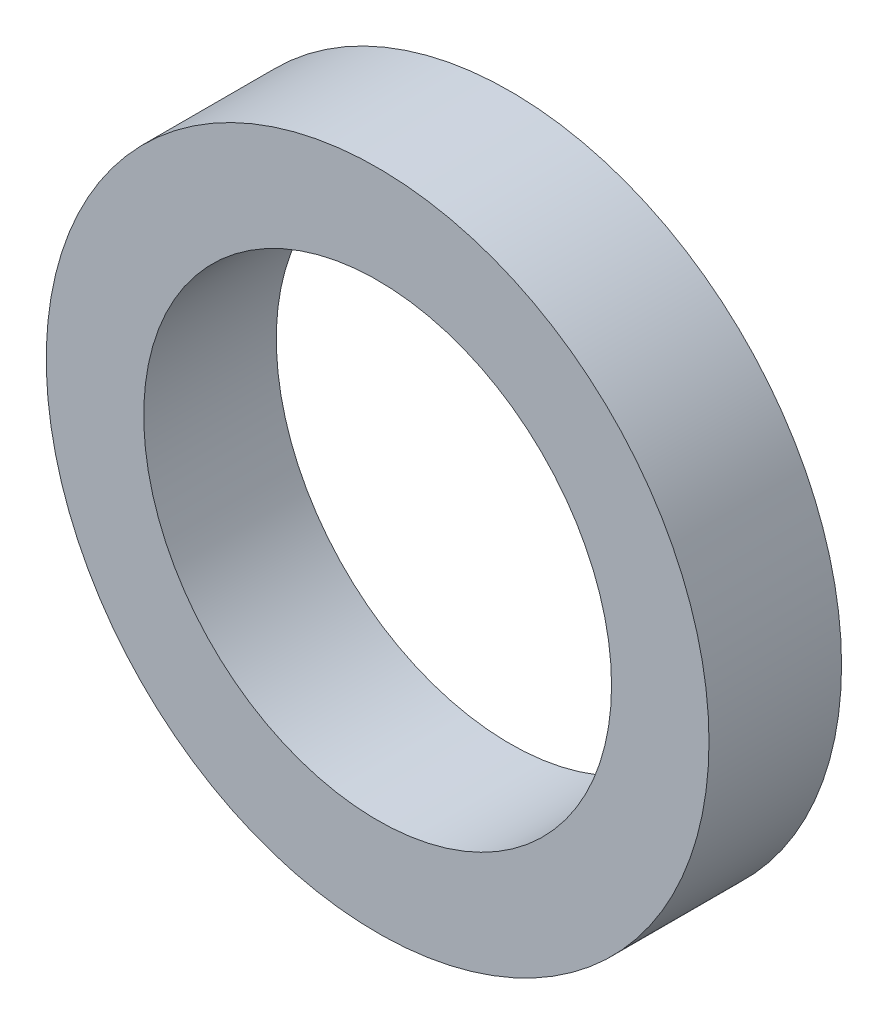
SolidWorks part; units mm, degrees
ref_plane "前视基准面" through (0, 0, 0) normal (0, 0, 1) x (1, 0, 0)
ref_plane "上视基准面" through (0, 0, 0) normal (0, 1, 0) x (1, 0, 0)
ref_plane "右视基准面" through (0, 0, 0) normal (1, 0, 0) x (0, 0, -1)
sketch "草图1" plane through (0, 0, 0) normal (0, 0, 1) x (1, 0, 0)
  circle A0 centre (0, 0) radius 42.5
  circle A1 centre (0, 0) radius 30
  dimension "D1" = 60
  dimension "D2" = 85
extrude "凸台-拉伸1" add sketch "草图1" along normal blind 17
